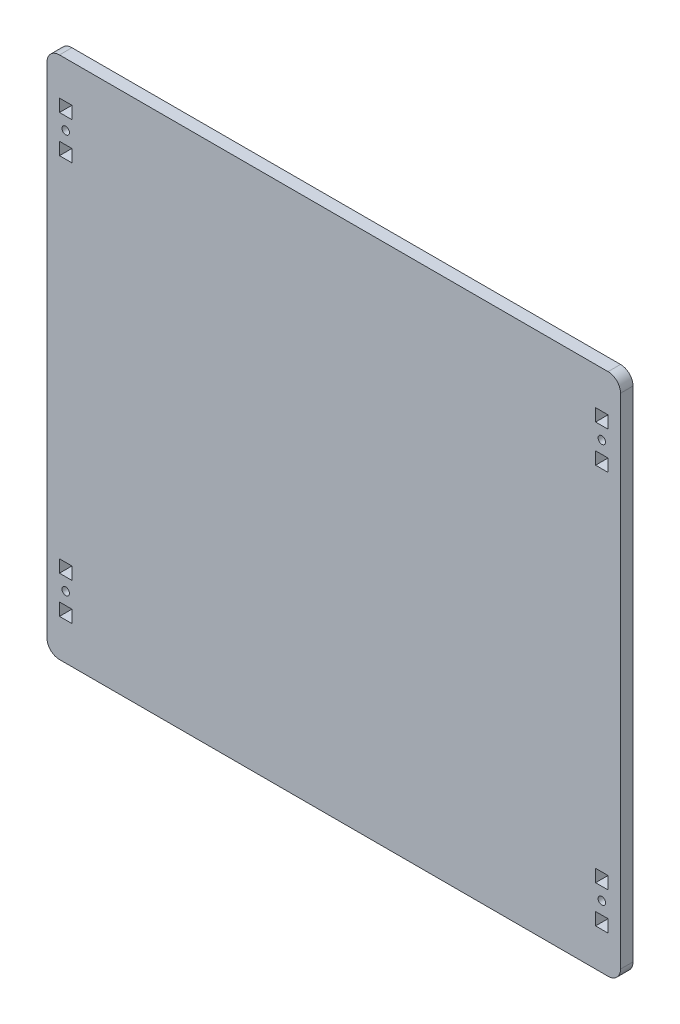
SolidWorks part; units mm, degrees
ref_plane "Plan de face" through (0, 0, 0) normal (0, 0, 1) x (1, 0, 0)
ref_plane "Plan de dessus" through (0, 0, 0) normal (0, 1, 0) x (1, 0, 0)
ref_plane "Plan de droite" through (0, 0, 0) normal (1, 0, 0) x (0, 0, -1)
sketch "Esquisse1" plane through (0, 0, 0) normal (0, 0, 1) x (1, 0, 0)
  line L0 (0, 105) -> (0, -105) construction
  line L1 (-115, 105) -> (115, 105)
  line L2 (-115, 105) -> (-115, -105)
  line L3 (-115, -105) -> (115, -105)
  line L4 (115, 105) -> (115, -105)
  line L5 (115, 0) -> (-115, 0) construction
  point P8 (0, 0)
  point P9 (0, 0)
  line B0 (105, 75) -> (105, 70)
  line B1 (105, 75) -> (110, 75)
  line B2 (110, 75) -> (110, 70)
  line B3 (105, 70) -> (110, 70)
  line B4 (105, 85) -> (105, 90)
  line B5 (105, 85) -> (110, 85)
  line B6 (110, 85) -> (110, 90)
  line B7 (105, 90) -> (110, 90)
  line B8 (107.5, 80) -> (101.2198, 80) construction
  circle B9 centre (107.5, 80) radius 1.5
  line B10 (105, -85) -> (105, -90)
  line B11 (105, -85) -> (110, -85)
  line B12 (110, -85) -> (110, -90)
  line B13 (105, -90) -> (110, -90)
  line B14 (105, -75) -> (105, -70)
  line B15 (105, -75) -> (110, -75)
  line B16 (110, -75) -> (110, -70)
  line B17 (105, -70) -> (110, -70)
  line B18 (107.5, -80) -> (101.2198, -80) construction
  circle B19 centre (107.5, -80) radius 1.5
  line B20 (-105, -85) -> (-105, -90)
  line B21 (-105, -85) -> (-110, -85)
  line B22 (-110, -85) -> (-110, -90)
  line B23 (-105, -90) -> (-110, -90)
  line B24 (-105, -75) -> (-105, -70)
  line B25 (-105, -75) -> (-110, -75)
  line B26 (-110, -75) -> (-110, -70)
  line B27 (-105, -70) -> (-110, -70)
  circle B28 centre (-107.5, -80) radius 1.5
  line B29 (-105, 75) -> (-105, 70)
  line B30 (-105, 75) -> (-110, 75)
  line B31 (-110, 75) -> (-110, 70)
  line B32 (-105, 70) -> (-110, 70)
  line B33 (-105, 85) -> (-105, 90)
  line B34 (-105, 85) -> (-110, 85)
  line B35 (-110, 85) -> (-110, 90)
  line B36 (-105, 90) -> (-110, 90)
  circle B37 centre (-107.5, 80) radius 1.5
  dimension "D1" = 160
  dimension "D2" = 210
  dimension "D3" = 5
  dimension "D4" = 15
sketch_block_instance "Trou M3 plots 5mm-52"
sketch_block "Trou M3 plots 5mm" parameters "D2"=3, "D1"=5, "D3"=5, "D4"=8
sketch_block_instance "Trou M3 plots 5mm-53"
sketch_block_instance "Trou M3 plots 5mm-55"
sketch_block_instance "Trou M3 plots 5mm-56"
extrude "Boss.-Extru.1" add sketch "Esquisse1" along normal blind 5
fillet "Congé1" radius 5 4 edges at (-115, -105, 2.5) (115, -105, 2.5) (115, 105, 2.5) (-115, 105, 2.5)
